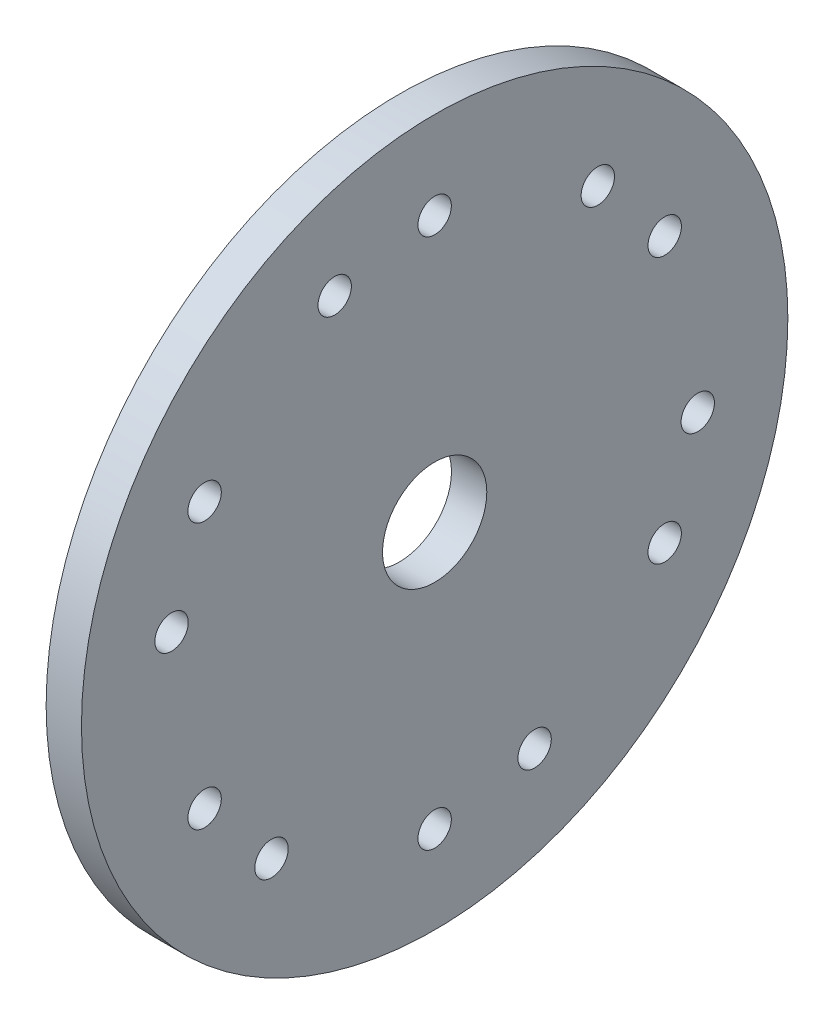
SolidWorks part; units mm, degrees
ref_plane "Front Plane" through (0, 0, 0) normal (0, 0, 1) x (1, 0, 0)
ref_plane "Top Plane" through (0, 0, 0) normal (0, 1, 0) x (1, 0, 0)
ref_plane "Right Plane" through (0, 0, 0) normal (1, 0, 0) x (0, 0, -1)
sketch "Sketch2" plane through (0, 0, 0) normal (1, 0, 0) x (0, 0, -1)
  line L0 (0, 0) -> (0, 95.505) construction
  line L1 (0, 0) -> (58.6573, 75.3692) construction
  circle A0 centre (0, 0) radius 31.75
  circle A1 centre (0, 0) radius 95.505 construction
  circle A2 centre (0, 0) radius 127
  circle A3 centre (0, 95.505) radius 6
  circle A4 centre (58.6573, 75.3692) radius 6
  circle A5 centre (0, 0) radius 31.75
  circle A6 centre (94.6003, -13.1141) radius 6
  circle A7 centre (82.7098, 47.7525) radius 6
  circle A8 centre (0, 0) radius 31.75
  circle A9 centre (35.943, -88.4834) radius 6
  circle A10 centre (82.7098, -47.7525) radius 6
  circle A11 centre (0, 0) radius 31.75
  circle A12 centre (-58.6573, -75.3692) radius 6
  circle A13 centre (0, -95.505) radius 6
  circle A14 centre (0, 0) radius 31.75
  circle A15 centre (-94.6003, 13.1141) radius 6
  circle A16 centre (-82.7098, -47.7525) radius 6
  circle A17 centre (0, 0) radius 31.75
  circle A18 centre (-35.943, 88.4834) radius 6
  circle A19 centre (-82.7098, 47.7525) radius 6
  point P37 (0, 0)
  dimension "D1" = 63.5
  dimension "D2" = 191.01
  dimension "D3" = 254
  dimension "D4" = 12
  dimension "D6" = 12
  dimension "D5" = 37.892
  dimension "D7" = 6
extrude "Boss-Extrude1" add sketch "Sketch2" along normal mid plane 12.7 contours A2 A19 A18 A16 A15 A13 A12 A10 A9 A7 A6 A4 A3 A0
scale "Scale1" scale about centroid uniform scaling yes scale factor 0.714782
scale "Scale2" scale about centroid uniform scaling yes scale factor 0.5
sketch "Sketch3" plane through (2.2694, 0, 0) normal (1, 0, 0) x (0, 0, -1)
  circle A0 centre (0, 0) radius 11.3472 construction
  circle A1 centre (0, 0) radius 45.3886
  circle A2 centre (0, 0) radius 45.3886
  circle A3 centre (0, 0) radius 11.3472
  circle A4 centre (0, 0) radius 10.05
  circle M14 centre (0, 0) radius 11.3472
  dimension "D2" = 20.1
  dimension "D1" = 0
extrude "Boss-Extrude2" add sketch "Sketch3" against normal up to surface (4.5389 mm away) contours A4 M14 up to face at (-2.2694, 17.0663, 27.4154)
scale "Scale3" scale about centroid uniform scaling yes scale factor 1.5
sketch "Sketch4" plane through (3.4041, 0, 0) normal (1, 0, 0) x (0, 0, -1)
  circle A0 centre (0, 0) radius 10.05
  circle A1 centre (0, 0) radius 15.075 construction
  circle A2 centre (0, 0) radius 15.075
  dimension "D1" = 20.1
extrude "Boss-Extrude3" add sketch "Sketch4" against normal up to surface (6.8083 mm away) up to face at (-3.4041, 25.5995, 41.123)
